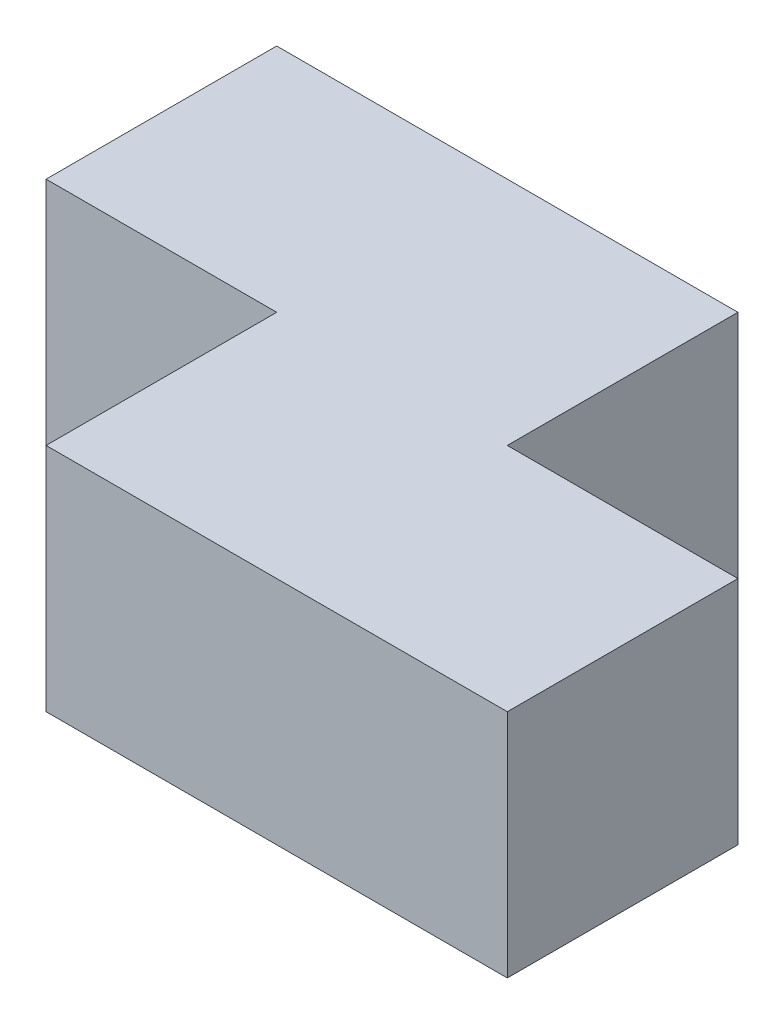
SolidWorks part; units mm, degrees
ref_plane "前基準面" through (0, 0, 0) normal (0, 0, 1) x (1, 0, 0)
ref_plane "上基準面" through (0, 0, 0) normal (0, 1, 0) x (1, 0, 0)
ref_plane "右基準面" through (0, 0, 0) normal (1, 0, 0) x (0, 0, -1)
sketch "草圖1" plane through (0, 0, 0) normal (0, 1, 0) x (1, 0, 0)
  line L1 (0, 0) -> (60, 0)
  line L2 (0, 0) -> (0, 30)
  line L3 (0, 30) -> (60, 30)
  line L4 (60, 0) -> (60, 30)
  line L5 (0, 30) -> (30, 30)
  line L6 (0, 30) -> (0, 60)
  line L7 (0, 60) -> (30, 60)
  line L8 (30, 30) -> (30, 60)
  dimension "D1" = 30
  dimension "D2" = 60
  dimension "D3" = 30
  dimension "D4" = 30
extrude "填料-伸長1" add sketch "草圖1" along normal blind 30 contours L1 L4 L3 L2 | L3 L8 L7 L6
sketch "草圖4" plane through (30, 0, 0) normal (1, 0, 0) x (0, 0, -1)
  line L4 (30, 0) -> (60, 0)
  line L5 (60, 0) -> (60, 30)
  line L6 (60, 30) -> (30, 30)
  line L7 (30, 30) -> (30, 0)
  line L8 (30, 0) -> (60, 0)
  line L9 (60, 0) -> (60, 30)
  line L10 (60, 30) -> (30, 30)
  line L11 (30, 30) -> (30, 0)
  dimension "D1" = 0
extrude "填料-伸長4" add sketch "草圖4" against normal blind 60
